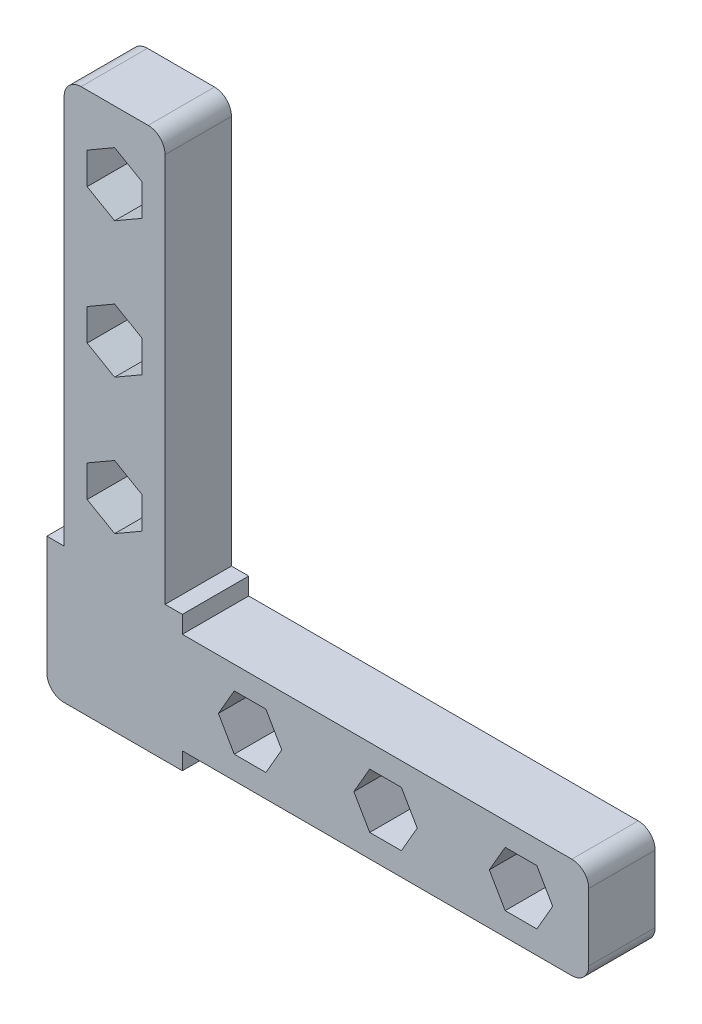
SolidWorks part; units mm, degrees
material "ABS"
ref_plane "Front" through (0, 0, 0) normal (0, 0, 1) x (1, 0, 0)
ref_plane "Top" through (0, 0, 0) normal (0, 1, 0) x (1, 0, 0)
ref_plane "Right" through (0, 0, 0) normal (1, 0, 0) x (0, 0, -1)
sketch "Sketch1" plane through (0, 0, 0) normal (0, 0, 1) x (1, 0, 0)
  line L0 (0, 0) -> (25.4, 0)
  line L1 (25.4, 0) -> (25.4, 3.2385)
  line L2 (25.4, 3.2385) -> (101.6, 3.2385)
  line L3 (101.6, 3.2385) -> (101.6, 22.1615)
  line L4 (101.6, 22.1615) -> (25.4, 22.1615)
  line L5 (25.4, 22.1615) -> (25.4, 25.4)
  line L6 (25.4, 25.4) -> (22.1615, 25.4)
  line L7 (22.1615, 25.4) -> (22.1615, 101.6)
  line L8 (22.1615, 101.6) -> (3.2385, 101.6)
  line L9 (3.2385, 101.6) -> (3.2385, 25.4)
  line L10 (3.2385, 25.4) -> (0, 25.4)
  line L11 (0, 25.4) -> (0, 0)
  dimension "D1" = 25.4
  dimension "D2" = 18.923
  dimension "D3" = 76.2
extrude "Boss-Extrude1" add sketch "Sketch1" along normal blind 12.446
sketch "Sketch2" plane through (0, 0, 12.446) normal (0, 0, 1) x (1, 0, 0)
  line L0 (12.7, 101.6) -> (12.7, 12.7) construction
  line L1 (22.1615, 101.6) -> (3.2385, 101.6) construction
  line L2 (12.7, 12.7) -> (101.6, 12.7) construction
  line L3 (101.6, 3.2385) -> (101.6, 22.1615) construction
  line L5 (17.8435, 85.9304) -> (17.8435, 91.8696)
  line L6 (17.8435, 91.8696) -> (12.7, 94.8392)
  line L7 (12.7, 94.8392) -> (7.5565, 91.8696)
  line L8 (7.5565, 91.8696) -> (7.5565, 85.9304)
  line L9 (7.5565, 85.9304) -> (12.7, 82.9608)
  line L10 (12.7, 82.9608) -> (17.8435, 85.9304)
  line L11 (17.8435, 60.5304) -> (17.8435, 66.4696)
  line L12 (17.8435, 66.4696) -> (12.7, 69.4392)
  line L13 (12.7, 69.4392) -> (7.5565, 66.4696)
  line L14 (7.5565, 66.4696) -> (7.5565, 60.5304)
  line L15 (7.5565, 60.5304) -> (12.7, 57.5608)
  line L16 (12.7, 57.5608) -> (17.8435, 60.5304)
  line L17 (17.8435, 35.1304) -> (17.8435, 41.0696)
  line L18 (17.8435, 41.0696) -> (12.7, 44.0392)
  line L19 (12.7, 44.0392) -> (7.5565, 41.0696)
  line L20 (7.5565, 41.0696) -> (7.5565, 35.1304)
  line L21 (7.5565, 35.1304) -> (12.7, 32.1608)
  line L22 (12.7, 32.1608) -> (17.8435, 35.1304)
  line L23 (41.0696, 7.5565) -> (44.0392, 12.7)
  line L24 (44.0392, 12.7) -> (41.0696, 17.8435)
  line L25 (41.0696, 17.8435) -> (35.1304, 17.8435)
  line L26 (35.1304, 17.8435) -> (32.1608, 12.7)
  line L27 (32.1608, 12.7) -> (35.1304, 7.5565)
  line L28 (35.1304, 7.5565) -> (41.0696, 7.5565)
  line L29 (66.4696, 7.5565) -> (69.4392, 12.7)
  line L30 (69.4392, 12.7) -> (66.4696, 17.8435)
  line L31 (66.4696, 17.8435) -> (60.5304, 17.8435)
  line L32 (60.5304, 17.8435) -> (57.5608, 12.7)
  line L33 (57.5608, 12.7) -> (60.5304, 7.5565)
  line L34 (60.5304, 7.5565) -> (66.4696, 7.5565)
  line L35 (91.8696, 7.5565) -> (94.8392, 12.7)
  line L36 (94.8392, 12.7) -> (91.8696, 17.8435)
  line L37 (91.8696, 17.8435) -> (85.9304, 17.8435)
  line L38 (85.9304, 17.8435) -> (82.9608, 12.7)
  line L39 (82.9608, 12.7) -> (85.9304, 7.5565)
  line L40 (85.9304, 7.5565) -> (91.8696, 7.5565)
  circle A0 centre (12.7, 88.9) radius 5.1435 construction
  circle A1 centre (12.7, 63.5) radius 5.1435 construction
  circle A2 centre (12.7, 38.1) radius 5.1435 construction
  circle A3 centre (38.1, 12.7) radius 5.1435 construction
  circle A4 centre (63.5, 12.7) radius 5.1435 construction
  circle A5 centre (88.9, 12.7) radius 5.1435 construction
  dimension "D1" = 10.287
  dimension "D2" = 25.4
  dimension "D3" = 25.4
  dimension "D4" = 25.4
  dimension "D5" = 25.4
  dimension "D6" = 25.4
  dimension "D7" = 25.4
extrude "Cut-Extrude1" cut sketch "Sketch2" against normal through all
fillet "Fillet1" radius 3.175 5 edges at (0, 0, 6.223) (101.6, 3.2385, 6.223) (101.6, 22.1615, 6.223) (22.1615, 101.6, 6.223) (3.2385, 101.6, 6.223)
